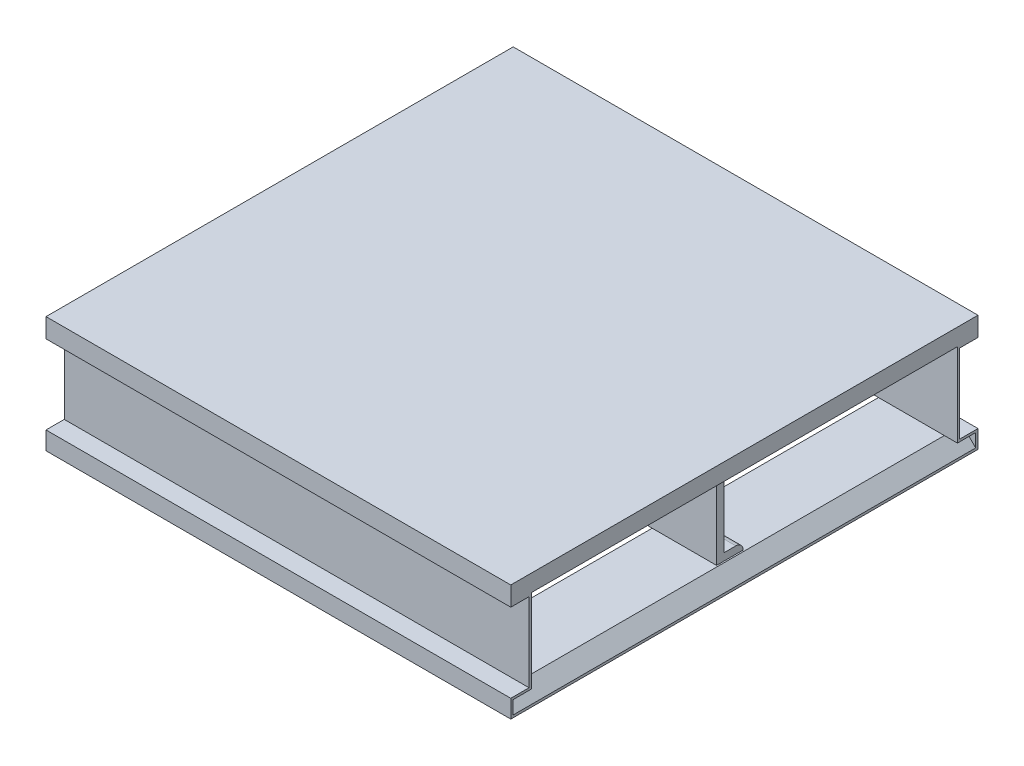
SolidWorks part; units mm, degrees
ref_plane "Front Plane" through (0, 0, 0) normal (0, 0, 1) x (1, 0, 0)
ref_plane "Top Plane" through (0, 0, 0) normal (0, 1, 0) x (1, 0, 0)
ref_plane "Right Plane" through (0, 0, 0) normal (1, 0, 0) x (0, 0, -1)
sketch "Sketch1" plane through (0, 0, 0) normal (0, 1, 0) x (1, 0, 0)
  line L0 (0, -306.3875) -> (0, 306.3875) construction
  line L1 (-304.8, 0) -> (304.8, 0) construction
  line L2 (304.8, -306.3875) -> (304.8, 306.3875) construction
  line L3 (304.8, 306.3875) -> (-304.8, 306.3875) construction
  point P4 (0, 0)
  point P8 (0, 0)
  point P10 (-304.8, 0)
  point P11 (304.8, -306.3875)
  point P14 (0, 306.3875)
  point P15 (-304.8, 306.3875)
  point P16 (304.8, 306.3875)
  point P22 (304.8, 0)
  dimension "Overall Depth" = 609.6
  dimension "Overall Width" = 612.775
sketch "Sketch2" plane through (0, 0, 0) normal (1, 0, 0) x (0, 0, -1)
  line L0 (0, 76.2) -> (0, -76.2) construction
  line L3 (-279.4, -53.975) -> (-279.4, 53.975) construction
  line L4 (-306.3875, 0) -> (306.3875, 0) construction
  point P0 (-19.05, 0)
  point P3 (0, 0)
  point P4 (-279.4, 0)
  point P11 (-279.4, 0)
  dimension "D1" = 19.05
  dimension "Overall Height" = 152.4
  dimension "Maximum Fork Width" = 260.35
  dimension "Maximum Fork Height" = 107.95
sketch "Sketch3" plane through (0, 0, 0) normal (0, 0, 1) x (1, 0, 0)
  line L0 (-304.8, 76.2) -> (304.8, 76.2) construction
  line L1 (304.8, 76.2) -> (304.8, -76.2) construction
  line L2 (304.8, -76.2) -> (-304.8, -76.2) construction
  line L3 (-304.8, -76.2) -> (-304.8, 76.2) construction
  line L4 (0, 76.2) -> (0, -76.2) construction
  line L5 (-304.8, 0) -> (304.8, 0) construction
  line L6 (-304.8, -76.2) -> (-304.8, -73.025)
  line L7 (-304.8, -73.025) -> (-287.655, -55.5625)
  line L8 (-287.655, -55.5625) -> (-201.295, -55.5625)
  line L9 (-201.295, -55.5625) -> (-184.15, -73.025)
  line L10 (-184.15, -73.025) -> (-184.15, -76.2)
  line L11 (-184.15, -76.2) -> (-304.8, -76.2)
  line L12 (-304.8, -73.025) -> (-184.15, -73.025) construction
  line L13 (-244.475, -55.5625) -> (-244.475, -76.2) construction
  line L14 (184.15, -73.025) -> (184.15, -76.2)
  line L15 (201.295, -55.5625) -> (184.15, -73.025)
  line L16 (287.655, -55.5625) -> (201.295, -55.5625)
  line L17 (304.8, -73.025) -> (287.655, -55.5625)
  line L18 (304.8, -76.2) -> (304.8, -73.025)
  line L19 (184.15, -76.2) -> (304.8, -76.2)
  line L20 (-60.325, -76.2) -> (60.325, -76.2)
  line L21 (-60.325, -76.2) -> (-60.325, -73.025)
  line L22 (-60.325, -73.025) -> (60.325, -73.025) construction
  line L23 (60.325, -73.025) -> (60.325, -76.2)
  line L24 (-43.18, -55.5625) -> (43.18, -55.5625)
  line L25 (-43.18, -55.5625) -> (-60.325, -73.025)
  line L26 (43.18, -55.5625) -> (60.325, -73.025)
  line L31 (-304.8, 73.66) -> (-304.8, 53.975)
  line L32 (-304.8, 53.975) -> (-184.15, 53.975)
  line L33 (-184.15, 53.975) -> (-184.15, 73.66)
  line L34 (-184.15, 73.66) -> (-304.8, 73.66)
  line L35 (0, 53.975) -> (-184.15, 53.975) construction
  point P26 (0, -76.2)
  point P31 (0, -55.5625)
  point P32 (-304.8, 73.66)
  point P33 (0, 53.975)
  dimension "D1" = 3.175
  dimension "D3" = 120.65
  dimension "D4" = 86.36
  dimension "D5" = 2.54
  dimension "D6" = 120.65
  dimension "D7" = 109.5375
extrude "Boss-Extrude1" add sketch "Sketch3" along normal mid plane 612.775
pattern_linear "LPattern1" count 3 spacing 244.475 along (1, 0, 0) of bodies 107
sketch "Sketch4" plane through (0, 0, 0) normal (1, 0, 0) x (0, 0, -1)
  line L0 (-306.3875, 76.2) -> (-306.3875, 50.927)
  line L1 (-306.3875, 50.927) -> (-282.448, 50.927)
  line L2 (-282.448, 50.927) -> (-282.448, -52.5145)
  line L3 (-282.448, -52.5145) -> (-306.3875, -52.5145)
  line L4 (-306.3875, -52.5145) -> (-306.3875, -76.2)
  line L5 (-306.3875, -76.2) -> (-303.3395, -76.2)
  line L6 (-306.3875, -76.2) -> (306.3875, -76.2) construction
  line L7 (-303.3395, -76.2) -> (-303.3395, -55.5625)
  line L8 (-306.3875, -55.5625) -> (306.3875, -55.5625) construction
  line L9 (-303.3395, -55.5625) -> (-279.4, -55.5625)
  line L10 (-279.4, -55.5625) -> (-279.4, 53.975)
  line L11 (-279.4, 53.975) -> (-303.3395, 53.975)
  line L12 (-306.3875, 53.975) -> (306.3875, 53.975) construction
  line L13 (-303.3395, 53.975) -> (-303.3395, 76.2)
  line L15 (-303.3395, 76.2) -> (-306.3875, 76.2)
  line L16 (-303.3395, 53.975) -> (-303.3395, 50.927) construction
  line L17 (-282.448, 50.927) -> (-279.4, 50.927) construction
  line L18 (-282.448, -52.5145) -> (-282.448, -55.5625) construction
  line L19 (-303.3395, 76.2) -> (0, 76.2) construction
  line L20 (0, 76.2) -> (0, -76.2) construction
  line L21 (303.3395, 53.975) -> (303.3395, 76.2)
  line L22 (279.4, 53.975) -> (303.3395, 53.975)
  line L23 (279.4, -55.5625) -> (279.4, 53.975)
  line L24 (303.3395, -55.5625) -> (279.4, -55.5625)
  line L25 (303.3395, -76.2) -> (303.3395, -55.5625)
  line L26 (306.3875, -76.2) -> (303.3395, -76.2)
  line L27 (306.3875, -52.5145) -> (306.3875, -76.2)
  line L28 (282.448, -52.5145) -> (306.3875, -52.5145)
  line L29 (282.448, 50.927) -> (282.448, -52.5145)
  line L30 (306.3875, 50.927) -> (282.448, 50.927)
  line L31 (306.3875, 76.2) -> (306.3875, 50.927)
  line L32 (303.3395, 76.2) -> (306.3875, 76.2)
  point P23 (-306.3875, 73.66)
  dimension "D1" = 3.048
extrude "Boss-Extrude2" add sketch "Sketch4" along normal mid plane 609.6
sketch "Sketch5" plane through (304.8, 0, 0) normal (1, 0, 0) x (0, 0, -1)
  line L0 (-303.3395, 76.2) -> (-303.3395, 73.66)
  line L1 (-303.3395, 73.66) -> (303.3395, 73.66)
  line L2 (303.3395, 73.66) -> (303.3395, 76.2)
  line L3 (303.3395, 76.2) -> (-303.3395, 76.2)
extrude "Boss-Extrude3" add sketch "Sketch5" against normal up to surface (609.6 mm away) up to face at (-304.8, -32.5437, 0)
sketch "Sketch6" plane through (0, 0, 0) normal (1, 0, 0) x (0, 0, -1)
  line L0 (-17.4625, 53.975) -> (-17.4625, -55.5625)
  line L3 (-279.4, 53.975) -> (279.4, 53.975) construction
  line L4 (-279.4, -55.5625) -> (279.4, -55.5625) construction
  line L5 (-279.4, 0) -> (-19.05, 0) construction
  line L6 (-279.4, -53.975) -> (-279.4, 53.975) construction
  line L7 (-19.05, 0) -> (-17.4625, 0) construction
  line L8 (-306.3875, 0) -> (306.3875, 0) construction
  line L9 (279.4, 0) -> (17.4625, 0) construction
  line L11 (279.4, -55.5625) -> (279.4, 53.975) construction
  line L12 (17.4625, 53.975) -> (17.4625, -55.5625) construction
  line L13 (-17.4625, 53.975) -> (17.4625, 53.975)
  line L14 (-17.4625, -55.5625) -> (17.4625, -55.5625)
  line L15 (7.9375, -46.0375) -> (-7.9375, -46.0375)
  line L16 (-7.9375, -46.0375) -> (-7.9375, 44.45)
  line L17 (-7.9375, 44.45) -> (7.9375, 44.45)
  line L18 (-7.9375, 44.45) -> (-7.9375, 53.975) construction
  line L19 (-7.9375, 44.45) -> (-17.4625, 44.45) construction
  arc A0 (17.4625, 53.975) -> (7.9375, 44.45) centre (7.9375, 53.975) cw
  arc A1 (17.4625, -55.5625) -> (7.9375, -46.0375) centre (7.9375, -55.5625) ccw
  point P4 (-19.05, 0)
  point P25 (17.4625, 0)
  dimension "D3" = 9.525
  dimension "D1" = 261.9375
  dimension "D2" = 261.9375
extrude "Boss-Extrude4" add sketch "Sketch6" along normal offset from surface 19.05 and the other way offset from surface (285.75 mm away) 19.05 up to face at (304.8, -0.5292, 0) other way up to face at (-304.8, -0.5292, 0)
sketch "Sketch7" plane through (0, 0, 0) normal (1, 0, 0) x (0, 0, -1)
  line L0 (-279.4, 53.975) -> (-279.4, -53.975) construction
  line L1 (-279.4, -53.975) -> (-19.05, -53.975) construction
  line L2 (-19.05, -53.975) -> (-19.05, 0) construction
  line L3 (0, 76.2) -> (306.3875, 76.2) construction
  line L4 (306.3875, 76.2) -> (306.3875, -76.2) construction
  line L5 (306.3875, -76.2) -> (0, -76.2) construction
  point P11 (-279.4, 53.975)
  point P12 (-279.4, -53.975)
  point P13 (-19.05, -53.975)
  point P20 (306.3875, 76.2)
  point P21 (306.3875, -76.2)
equation "\"D1@Boss-Extrude1\"=\"Overall Width@sketch1\""
equation "\"D1@Boss-Extrude2\"=\"Overall Depth@sketch1\""
equation "\"D2@Sketch6\"=\"D1@Sketch6\""
